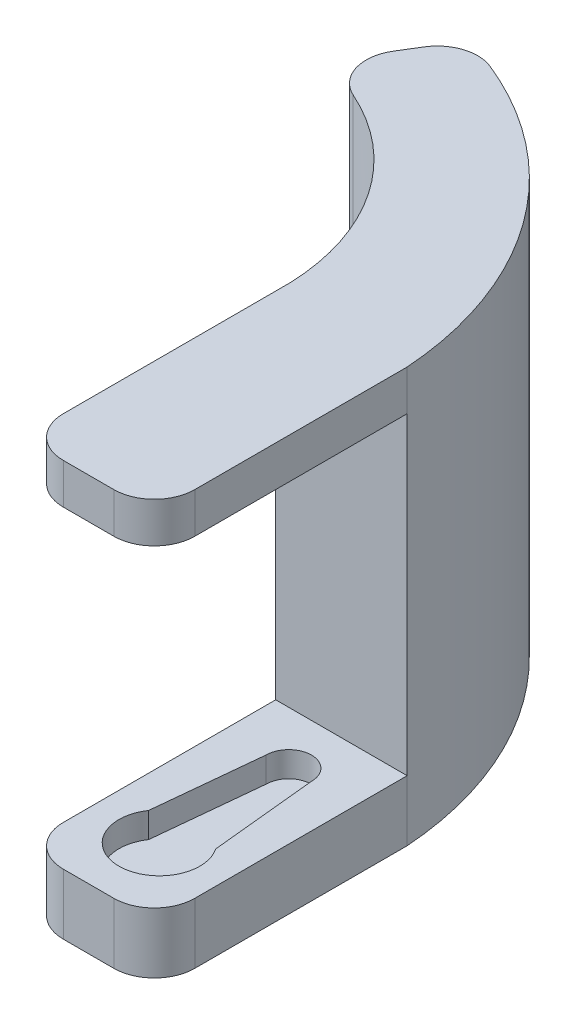
SolidWorks part; units mm, degrees
material "PLA - 20%"
ref_plane "Front Plane" through (0, 0, 0) normal (0, 0, 1) x (1, 0, 0)
ref_plane "Top Plane" through (0, 0, 0) normal (0, 1, 0) x (1, 0, 0)
ref_plane "Right Plane" through (0, 0, 0) normal (1, 0, 0) x (0, 0, -1)
sketch "Sketch1" plane through (0, 0, 0) normal (0, 1, 0) x (1, 0, 0)
  line L1 (0, 0) -> (13, 0)
  line L2 (0, 0) -> (0, -25)
  line L3 (0, -25) -> (13, -25)
  line L4 (13, 0) -> (13, -25)
  dimension "D1" = 13
  dimension "D2" = 25
extrude "Boss-Extrude1" add sketch "Sketch1" along normal blind 6
ref_plane "Plane1" through (0, 37, 0) normal (0, 1, 0) x (1, 0, 0)
sketch "Sketch2" plane through (0, 37, 0) normal (0, 1, 0) x (1, 0, 0)
  line L1 (0, 0) -> (13, 0)
  line L2 (0, 0) -> (0, -25)
  line L3 (0, -25) -> (13, -25)
  line L4 (13, 0) -> (13, -25)
extrude "Boss-Extrude2" add sketch "Sketch2" along normal blind 4 separate body
sketch "Sketch3" plane through (0, 6, 0) normal (0, 1, 0) x (1, 0, 0)
  line L0 (0, -25) -> (13, -25) construction
  line L3 (3.1928, -15.75) -> (4.25, -5.2077)
  line L4 (3.1928, -15.75) -> (3.1928, -20.25)
  line L5 (9.8072, -20.25) -> (9.8072, -15.75)
  line L6 (9.8072, -15.75) -> (8.75, -5.2077)
  line L7 (0, -25) -> (13, -25) construction
  circle A1 centre (6.5, -18) radius 4
  arc A2 (4.25, -5.2077) -> (8.75, -5.2077) centre (6.5, -5.2077) cw
  point P0 (6.5, -25)
  dimension "D2" = 4.5
  dimension "D3" = 8
  dimension "D5" = 2.25
  dimension "D1" = 7
  dimension "D4" = 4.5
extrude "Cut-Extrude1" cut sketch "Sketch3" against normal blind 2.5 contours A2 L3 A1 L6 | L5 A1 L4 | L4 A1 | L5 A1
sketch "Sketch4" plane through (0, 0, 0) normal (0, -1, 0) x (1, 0, 0)
  line L0 (13, 0) -> (0, 0) construction
  line L1 (-17.3765, -22.0438) -> (-11.8946, -30.9835)
  line L2 (0, 0) -> (13, 0)
  arc A0 (0, 0) -> (-17.3765, -22.0438) centre (-21.8207, -0.67) cw
  arc A1 (13, 0) -> (-11.8946, -30.9835) centre (-21.7492, 2.4274) cw
extrude "Boss-Extrude3" add sketch "Sketch4" against normal through all
ref_plane "Plane2" through (0, 9, 0) normal (0, -1, 0) x (-1, 0, 0)
sketch "Sketch5" plane through (0, 9, 0) normal (0, -1, 0) x (-1, 0, 0)
  line L0 (7.3011, 16.9725) -> (1.7207, 26.0728)
  line L4 (17.3765, 22.0438) -> (11.8946, 30.9835)
  line L5 (-13, 0) -> (-13, -25)
  line L6 (-13, -25) -> (0, -25)
  line L7 (0, -25) -> (0, 0)
  line L8 (17.3765, 22.0438) -> (11.8946, 30.9835)
  line L9 (-13, 0) -> (-13, -25)
  line L10 (-13, -25) -> (0, -25)
  line L11 (0, -25) -> (0, 0)
  arc A0 (17.3765, 22.0438) -> (0, 0) centre (21.8207, 0.67) ccw construction
  arc A2 (17.3765, 22.0438) -> (0, 0) centre (21.8207, 0.67) ccw
  arc A3 (11.8946, 30.9835) -> (-13, 0) centre (21.7492, -2.4274) ccw
  arc A4 (17.3765, 22.0438) -> (0, 0) centre (21.8207, 0.67) ccw
  arc A5 (11.8946, 30.9835) -> (-13, 0) centre (21.7492, -2.4274) ccw
  dimension "D1" = 0
extrude "Cut-Extrude2" cut sketch "Sketch5" against normal blind 18 contours L8 A5 L0 A4
fillet "Fillet2" radius 4 4 edges at (-11.8946, 34, -30.9835) (-17.3765, 34, -22.0438) (-17.3765, 4.5, -22.0438) (-11.8946, 4.5, -30.9835)
fillet "Fillet3" radius 4 4 edges at (0, 39, 25) (13, 39, 25) (0, 3, 25) (13, 3, 25)
